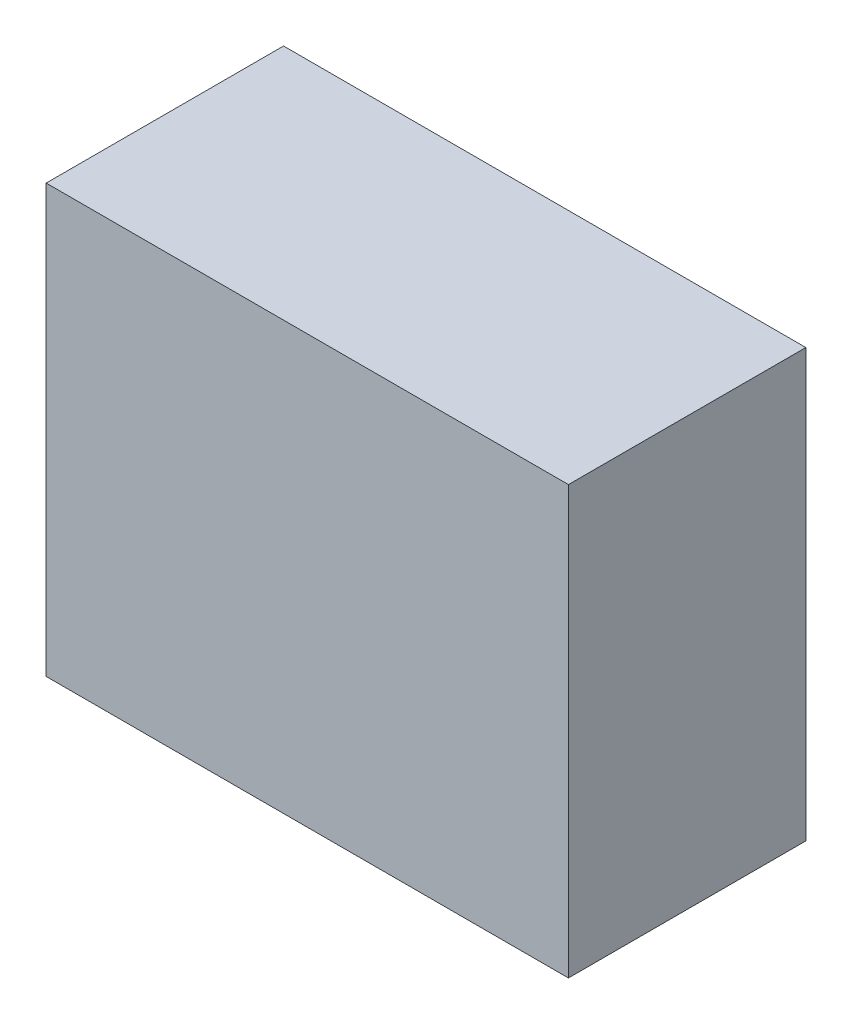
SolidWorks part; units mm, degrees
ref_plane "Front Plane" through (0, 0, 0) normal (0, 0, 1) x (1, 0, 0)
ref_plane "Top Plane" through (0, 0, 0) normal (0, 1, 0) x (1, 0, 0)
ref_plane "Right Plane" through (0, 0, 0) normal (1, 0, 0) x (0, 0, -1)
sketch "Sketch1" plane through (0, 0, 0) normal (0, 0, 1) x (1, 0, 0)
  line L1 (-104.775, 85.725) -> (104.775, 85.725)
  line L2 (-104.775, 85.725) -> (-104.775, -85.725)
  line L3 (-104.775, -85.725) -> (104.775, -85.725)
  line L4 (104.775, 85.725) -> (104.775, -85.725)
  line L5 (-104.775, 85.725) -> (104.775, -85.725) construction
  line L6 (-104.775, -85.725) -> (104.775, 85.725) construction
  point P0 (0, 0)
  dimension "D1" = 209.55
  dimension "D2" = 171.45
extrude "Boss-Extrude1" add sketch "Sketch1" along normal blind 95.25
